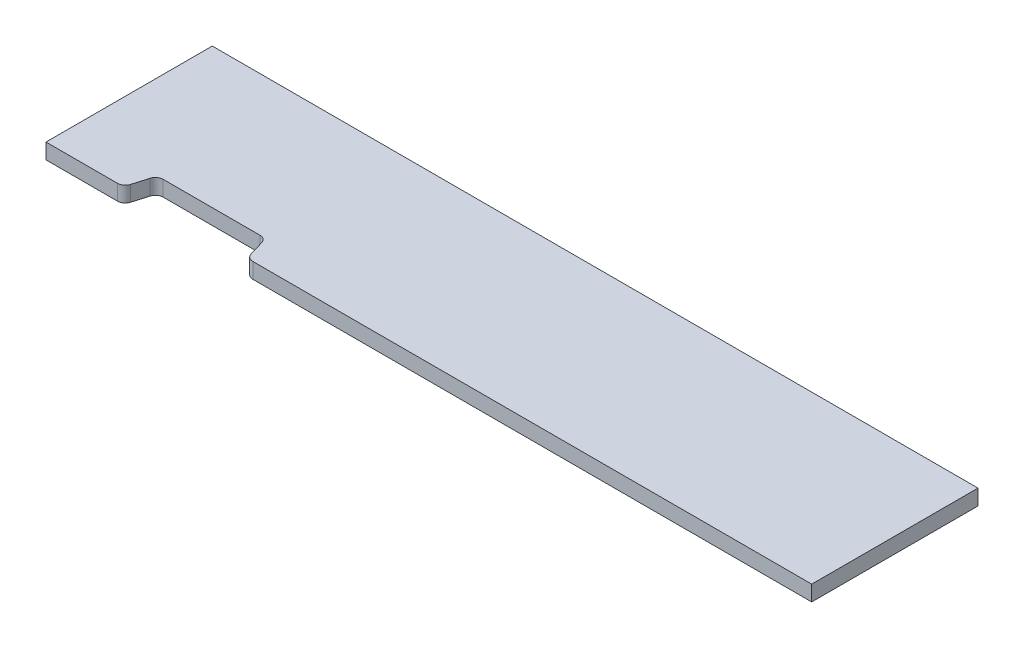
SolidWorks part; units mm, degrees
ref_plane "Front Plane" through (0, 0, 0) normal (0, 0, 1) x (1, 0, 0)
ref_plane "Top Plane" through (0, 0, 0) normal (0, 1, 0) x (1, 0, 0)
ref_plane "Right Plane" through (0, 0, 0) normal (1, 0, 0) x (0, 0, -1)
sketch "Sketch1" plane through (0, 0, 0) normal (0, 1, 0) x (1, 0, 0)
  line L1 (-314.325, -68.2625) -> (314.325, -68.2625)
  line L2 (-314.325, -68.2625) -> (-314.325, 68.2625)
  line L3 (-314.325, 68.2625) -> (314.325, 68.2625)
  line L4 (314.325, -68.2625) -> (314.325, 68.2625)
  line L5 (-314.325, -68.2625) -> (314.325, 68.2625) construction
  line L6 (-314.325, 68.2625) -> (314.325, -68.2625) construction
  point P0 (0, 0)
  dimension "D1" = 628.65
  dimension "D2" = 136.525
extrude "Boss-Extrude1" add sketch "Sketch1" against normal blind 12.7
sketch "Sketch2" plane through (0, 0, 0) normal (0, 1, 0) x (1, 0, 0)
  line L0 (-250.825, -68.2625) -> (-244.475, -46.6725)
  line L1 (-314.325, -68.2625) -> (314.325, -68.2625) construction
  line L2 (-244.475, -46.6725) -> (-155.575, -46.6725)
  line L3 (-155.575, -46.6725) -> (-149.225, -68.2625)
  line L4 (-149.225, -68.2625) -> (-250.825, -68.2625)
  line L5 (-200.025, -68.2625) -> (-200.025, -46.6725) construction
  dimension "D1" = 101.6
  dimension "D2" = 63.5
  dimension "D3" = 88.9
  dimension "D4" = 21.59
extrude "Cut-Extrude1" cut sketch "Sketch2" against normal through all
fillet "Fillet1" radius 6.35 4 edges at (-155.575, -6.35, 46.6725) (-149.225, -6.35, 68.2625) (-244.475, -6.35, 46.6725) (-250.825, -6.35, 68.2625)
